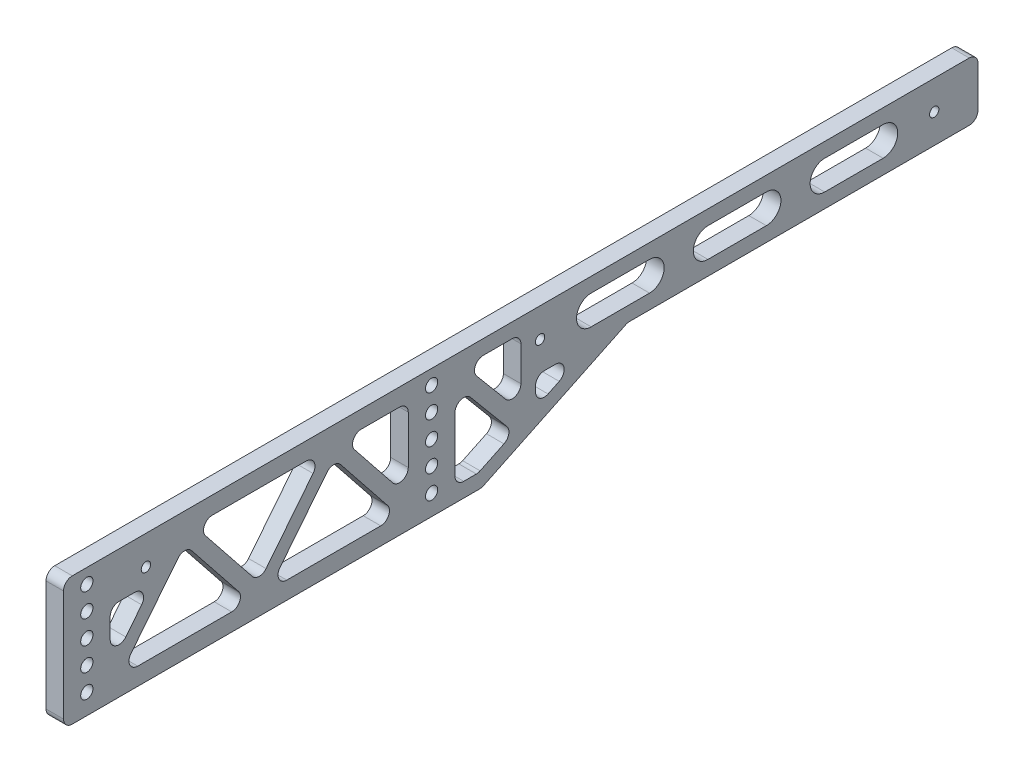
SolidWorks part; units mm, degrees
material "Thornel Mat VMA"
ref_plane "前视基准面" through (0, 0, 0) normal (0, 0, 1) x (1, 0, 0)
ref_plane "上视基准面" through (0, 0, 0) normal (0, 1, 0) x (1, 0, 0)
ref_plane "右视基准面" through (0, 0, 0) normal (1, 0, 0) x (0, 0, -1)
other "Configuration Table"
sketch "草图1" plane through (0, 0, 0) normal (1, 0, 0) x (0, 0, -1)
  line L0 (0, -34) -> (135, -34) construction
  line L1 (285, 10) -> (-28.22, 10)
  line L2 (-28.22, 10) -> (-28.22, -34)
  line L3 (-28.22, -34) -> (115, -34)
  line L4 (115, -34) -> (165, -10)
  line L5 (165, -10) -> (285, -10)
  line L6 (285, -10) -> (285, 10)
  circle A0 centre (0, 0) radius 1.6
  circle A1 centre (135, 0) radius 1.6
  circle A2 centre (270, 0) radius 1.6
  circle A3 centre (97.86, -27) radius 2.1
  circle A4 centre (97.86, -19) radius 2.1
  circle A5 centre (97.86, -11) radius 2.1
  circle A6 centre (97.86, -3) radius 2.1
  circle A7 centre (97.86, 5) radius 2.1
  circle A8 centre (-20.23, -27) radius 2.1
  circle A9 centre (-20.23, -19) radius 2.1
  circle A10 centre (-20.23, -11) radius 2.1
  circle A11 centre (-20.23, -3) radius 2.1
  circle A12 centre (-20.23, 5) radius 2.1
  dimension "D1" = 3.2
  dimension "D3" = 270
  dimension "D5" = 187.14
  dimension "D8" = 4.2
  dimension "D9" = 7
  dimension "D11" = 32
  dimension "D16" = 118.09
  dimension "D4" = 34
  dimension "D6" = 15
  dimension "D7" = 10
  dimension "D12" = 20
  dimension "D13" = 120
  dimension "D14" = 50
  dimension "D17" = 28.22
  dimension "D2" = 3
  dimension "D10" = 5
  dimension "D15" = 2
extrude "凸台-拉伸1" add sketch "草图1" along normal blind 6
sketch "草图2" plane through (6, 0, 0) normal (1, 0, 0) x (0, 0, -1)
  line L0 (135, 0) -> (270, 0) construction
  line L1 (192.5, 0) -> (212.5, 0) construction
  line L2 (192.5, 5) -> (212.5, 5)
  line L3 (192.5, -5) -> (212.5, -5)
  line L4 (232.5, -5) -> (252.5, -5)
  line L5 (232.5, 5) -> (252.5, 5)
  line L6 (232.5, 0) -> (252.5, 0) construction
  line L7 (152.5, -5) -> (172.5, -5)
  line L8 (152.5, 5) -> (172.5, 5)
  line L9 (152.5, 0) -> (172.5, 0) construction
  line L10 (105.86, 5) -> (105.86, -29)
  line L11 (105.86, -29) -> (113.8621, -29)
  line L12 (113.8621, -29) -> (128.4455, -22)
  line L13 (128.4455, -22) -> (128.4455, 5)
  line L14 (128.4455, 5) -> (105.86, 5)
  line L15 (133.4455, -10) -> (133.4455, -19.6)
  line L16 (133.4455, -19.6) -> (153.4455, -10)
  line L17 (153.4455, -10) -> (133.4455, -10)
  line L18 (105.86, 5) -> (128.4455, -22)
  line L19 (115, -34) -> (165, -10) construction
  line L20 (165, -10) -> (285, -10) construction
  line L21 (285, 10) -> (-28.22, 10) construction
  line L22 (-28.22, -34) -> (115, -34) construction
  line L23 (105.86, 1.1036) -> (126.1199, -23.1163)
  line L24 (109.1193, 5) -> (128.4455, -18.1036)
  line L25 (107.7776, 6.604) -> (130.363, -20.396) construction
  line L26 (103.9424, 3.396) -> (126.5279, -23.604) construction
  line L27 (0, -5.6) -> (-12.23, -5.6)
  line L28 (-12.23, 4) -> (89.86, 4)
  line L29 (-12.23, 4) -> (-12.23, -28)
  line L30 (-12.23, -28) -> (89.86, -28)
  line L31 (89.86, 4) -> (89.86, -28)
  line L32 (5.6, 0) -> (5.6, 4)
  line L33 (38.815, -28) -> (38.815, 4) construction
  line L34 (38.815, 4) -> (89.86, 4) construction
  line L35 (64.3375, 4) -> (38.815, -28) construction
  line L36 (64.3375, 4) -> (89.86, -28) construction
  line L37 (38.815, 4) -> (-12.23, 4) construction
  line L38 (13.2925, 4) -> (38.815, -28) construction
  line L39 (13.2925, 4) -> (-12.23, -28) construction
  line L40 (64.3375, 8.0094) -> (91.8145, -26.4412)
  line L41 (64.3375, 8.0094) -> (38.815, -23.9906)
  line L42 (13.2925, 8.0094) -> (38.815, -23.9906)
  line L43 (13.2925, 8.0094) -> (-14.1845, -26.4412)
  line L44 (64.3375, -0.0094) -> (87.9055, -29.5588)
  line L45 (64.3375, -0.0094) -> (38.815, -32.0094)
  line L46 (13.2925, -0.0094) -> (38.815, -32.0094)
  line L47 (13.2925, -0.0094) -> (-10.2755, -29.5588)
  arc A0 (192.5, 5) -> (192.5, -5) centre (192.5, 0) ccw
  arc A1 (212.5, -5) -> (212.5, 5) centre (212.5, 0) ccw
  arc A2 (232.5, 5) -> (232.5, -5) centre (232.5, 0) ccw
  arc A3 (252.5, -5) -> (252.5, 5) centre (252.5, 0) ccw
  arc A4 (152.5, 5) -> (152.5, -5) centre (152.5, 0) ccw
  arc A5 (172.5, -5) -> (172.5, 5) centre (172.5, 0) ccw
  circle A6 centre (97.86, -3) radius 2.1 construction
  circle A7 centre (97.86, -19) radius 2.1 construction
  circle A8 centre (-20.23, -11) radius 2.1 construction
  circle A11 centre (0, 0) radius 5.6
  circle A12 centre (0, 0) radius 5.6
  point P6 (202.5, 0)
  point P14 (242.5, 0)
  point P21 (162.5, 0)
  dimension "D1" = 5
  dimension "D2" = 20
  dimension "D5" = 5
  dimension "D6" = 5
  dimension "D7" = 20
  dimension "D8" = 5
  dimension "D9" = 8
  dimension "D10" = 5
  dimension "D13" = 6
  dimension "D14" = 6
  dimension "D15" = 8
  dimension "D16" = 8
  dimension "D18" = 2.5
  dimension "D11" = 2.5
  dimension "D12" = 2.5
  dimension "D17" = 4
  dimension "D19" = 2.5
  dimension "D3" = 2
  dimension "D4" = 2
extrude "切除-拉伸1" cut sketch "草图2" against normal blind 10 contours L46 L47 L30 | A12 L27 L29 L43 | L28 L42 L41 | L44 L45 L30 | L28 L40 L31 | L23 L10 L11 L12 | L14 L24 L13 | L16 L17 L15 | L7 A5 L8 A4 | L3 A1 L2 A0 | L4 A3 L5 A2
fillet "圆角1" radius 3 25 edges at (3, -23.1163, -126.1199) (3, -29, -113.8621) (3, -29, -105.86) (3, 1.1036, -105.86) (3, -18.1036, -128.4455) (3, 5, -109.1193) (3, 5, -128.4455) (3, 4, -61.1397) (3, -23.9906, -38.815) (3, -28, -86.6622) (3, -28, -42.0128) (3, -0.0094, -64.3375) (3, -28, -35.6172) (3, -28, 9.0322) (3, -0.0094, -13.2925) (3, 4, -89.86) (3, -23.9906, -89.86) (3, 4, -67.5353) (3, -4.5316, -3.2901) (3, -23.9906, 12.23) (3, -5.6, 12.23) (3, -10, -133.4455) (3, -10, -153.4455) (3, -19.6, -133.4455) (3, 4, -16.4903)
fillet "圆角2" radius 3 6 edges at (3, -10, -285) (3, -10, -165) (3, -34, -115) (3, -34, 28.22) (3, 10, -285) (3, 10, 28.22)
